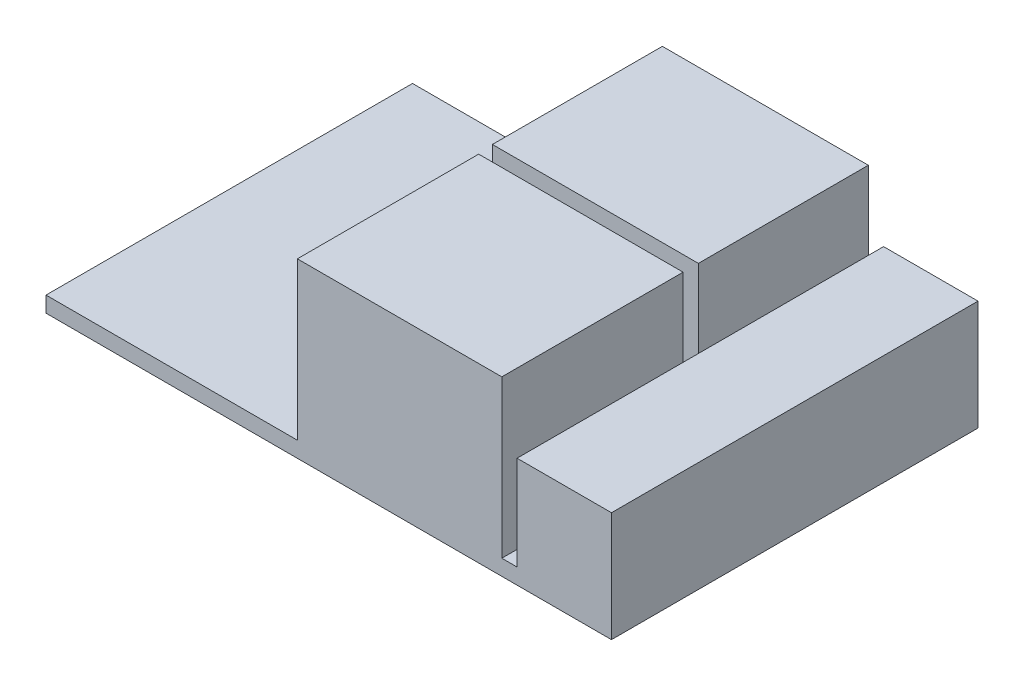
SolidWorks part; units mm, degrees
ref_plane "前视基准面" through (0, 0, 0) normal (0, 0, 1) x (1, 0, 0)
ref_plane "上视基准面" through (0, 0, 0) normal (0, 1, 0) x (1, 0, 0)
ref_plane "右视基准面" through (0, 0, 0) normal (1, 0, 0) x (0, 0, -1)
other "Configuration Table"
sketch "草图1" plane through (0, 0, 0) normal (0, 1, 0) x (1, 0, 0)
  line L0 (203.5758, 850.9118) -> (1017.879, 850.9118) construction
  line L3 (0, 137.1079) -> (54, 137.1079)
  line L4 (0, 137.1079) -> (0, 102.1079)
  line L5 (0, 102.1079) -> (54, 102.1079)
  line L6 (54, 137.1079) -> (54, 102.1079)
  line L7 (54, 137.1079) -> (47.2787, 137.1079)
  line L8 (54, 137.1079) -> (54, 102.1079)
  line L9 (54, 102.1079) -> (47.2787, 102.1079)
  line L10 (47.2787, 137.1079) -> (47.2787, 102.1079) construction
  line L11 (54, 137.1079) -> (47.2787, 102.1079) construction
  line L12 (54, 102.1079) -> (47.2787, 137.1079) construction
  line L13 (23.802, 137.1079) -> (45.2592, 137.1079)
  line L14 (23.802, 137.1079) -> (23.802, 119.6079) construction
  line L15 (23.802, 119.6079) -> (45.2592, 119.6079) construction
  line L16 (45.2592, 137.1079) -> (45.2592, 119.6079) construction
  line L17 (23.802, 137.1079) -> (45.2592, 119.6079) construction
  line L18 (23.802, 119.6079) -> (45.2592, 137.1079) construction
  line L19 (23.802, 118.4725) -> (45.2592, 118.4725) construction
  line L20 (23.802, 118.4725) -> (23.802, 102.1079) construction
  line L21 (23.802, 102.1079) -> (45.2592, 102.1079)
  line L22 (45.2592, 118.4725) -> (45.2592, 102.1079) construction
  line L23 (23.802, 118.4725) -> (45.2592, 102.1079) construction
  line L24 (23.802, 102.1079) -> (45.2592, 118.4725) construction
  point P9 (50.6394, 119.6079)
  point P14 (34.5306, 128.3579)
  point P19 (34.5306, 110.2902)
  dimension "D1" = 35
  dimension "D2" = 54
  dimension "D3" = 0
extrude "凸台-拉伸1" add sketch "草图1" along normal blind 1.5 contours L6 L3 L4 L5
sketch "草图2" plane through (0, 1.5, 0) normal (0, 1, 0) x (1, 0, 0)
  line L0 (0, 102.1079) -> (54, 102.1079) construction
  line L1 (54, 137.1079) -> (44.9839, 137.1079)
  line L2 (54, 137.1079) -> (54, 102.1079)
  line L3 (54, 102.1079) -> (44.9839, 102.1079)
  line L4 (44.9839, 137.1079) -> (44.9839, 102.1079)
  line L5 (54, 137.1079) -> (44.9839, 102.1079) construction
  line L6 (54, 102.1079) -> (44.9839, 137.1079) construction
  line L7 (0, 137.1079) -> (54, 137.1079) construction
  line L8 (23.8587, 137.1079) -> (43.527, 137.1079)
  line L9 (23.8587, 137.1079) -> (23.8587, 120.8778)
  line L10 (23.8587, 120.8778) -> (43.527, 120.8778)
  line L11 (43.527, 137.1079) -> (43.527, 120.8778)
  line L12 (23.8587, 137.1079) -> (43.527, 120.8778) construction
  line L13 (23.8587, 120.8778) -> (43.527, 137.1079) construction
  line L15 (24.0044, 119.4209) -> (43.527, 119.4209)
  line L16 (24.0044, 119.4209) -> (24.0044, 102.1079)
  line L17 (24.0044, 102.1079) -> (43.527, 102.1079)
  line L18 (43.527, 119.4209) -> (43.527, 102.1079)
  line L19 (24.0044, 119.4209) -> (43.527, 102.1079) construction
  line L20 (24.0044, 102.1079) -> (43.527, 119.4209) construction
  point P4 (49.492, 119.6079)
  point P12 (33.6928, 128.9929)
  point P19 (33.7657, 110.7644)
extrude "凸台-拉伸2" add sketch "草图2" along normal blind 9
sketch "草图3" plane through (0, 10.5, 0) normal (0, 1, 0) x (1, 0, 0)
  line L1 (23.8587, 137.1079) -> (43.527, 137.1079)
  line L2 (23.8587, 137.1079) -> (23.8587, 120.8778)
  line L3 (23.8587, 120.8778) -> (43.527, 120.8778)
  line L4 (43.527, 137.1079) -> (43.527, 120.8778)
  line L5 (23.8587, 137.1079) -> (43.527, 120.8778) construction
  line L6 (23.8587, 120.8778) -> (43.527, 137.1079) construction
  line L7 (43.527, 119.4209) -> (24.0044, 119.4209)
  line L8 (43.527, 119.4209) -> (43.527, 102.1079)
  line L9 (43.527, 102.1079) -> (24.0044, 102.1079)
  line L10 (24.0044, 119.4209) -> (24.0044, 102.1079)
  line L11 (43.527, 119.4209) -> (24.0044, 102.1079) construction
  line L12 (43.527, 102.1079) -> (24.0044, 119.4209) construction
  point P4 (33.6928, 128.9929)
  point P11 (33.7657, 110.7644)
extrude "凸台-拉伸3" add sketch "草图3" along normal blind 6
